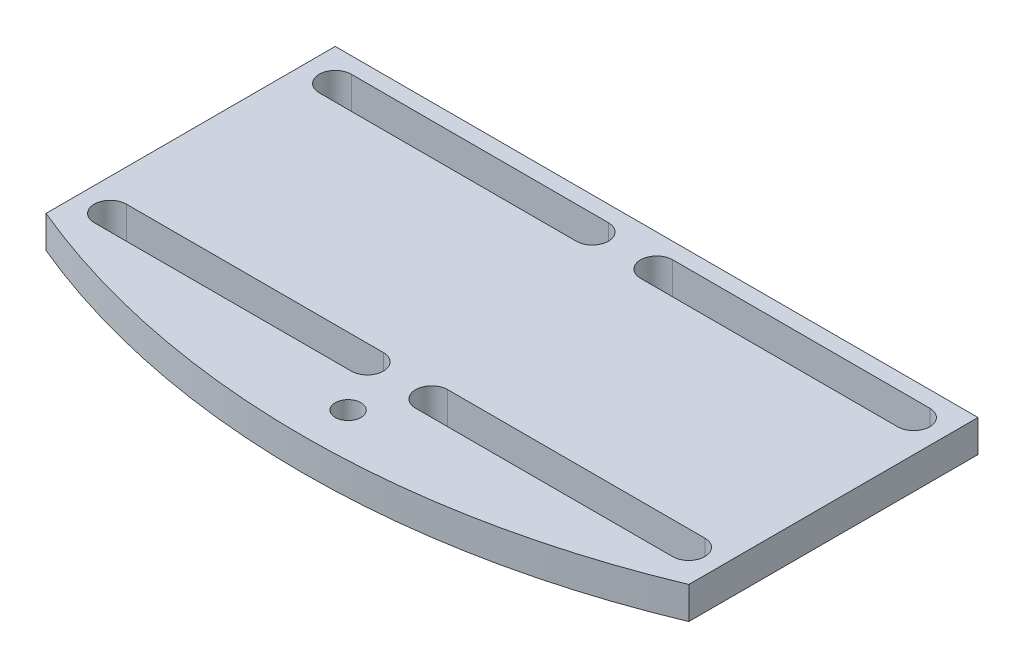
SolidWorks part; units mm, degrees
ref_plane "Front Plane" through (0, 0, 0) normal (0, 0, 1) x (1, 0, 0)
ref_plane "Top Plane" through (0, 0, 0) normal (0, 1, 0) x (1, 0, 0)
ref_plane "Right Plane" through (0, 0, 0) normal (1, 0, 0) x (0, 0, -1)
sketch "Sketch1" plane through (0, 0, 0) normal (0, 1, 0) x (1, 0, 0)
  line L2 (50, -40) -> (50, 5)
  line L3 (50, 5) -> (-50, 5)
  line L4 (-50, -40) -> (-50, 5)
  arc A0 (-50, -40) -> (50, -40) centre (0, 80) ccw
  point P0 (0, 5)
  point P6 (0, -50)
  dimension "D1" = 100
  dimension "D2" = 45
  dimension "D3" = 5
  dimension "D4" = 10
extrude "Boss-Extrude1" add sketch "Sketch1" along normal blind 5
sketch "Sketch2" plane through (0, 5, 0) normal (0, 1, 0) x (1, 0, 0)
  line L0 (0, 20) -> (0, -20) construction
  line L3 (-45, 0) -> (-5, 0) construction
  line L4 (-45, -35) -> (-5, -35) construction
  line L5 (-45, -32.5) -> (-5, -32.5)
  line L6 (-45, -37.5) -> (-5, -37.5)
  line L7 (-45, 2.5) -> (-5, 2.5)
  line L8 (-45, -2.5) -> (-5, -2.5)
  arc A8 (-45, -32.5) -> (-45, -37.5) centre (-45, -35) ccw
  arc A9 (-5, -37.5) -> (-5, -32.5) centre (-5, -35) ccw
  arc A10 (-45, 2.5) -> (-45, -2.5) centre (-45, 0) ccw
  arc A11 (-5, -2.5) -> (-5, 2.5) centre (-5, 0) ccw
  point P7 (-25, -35)
  point P11 (0, 0)
  point P15 (-25, 0)
  dimension "D4" = 40
  dimension "D2" = 2.5
  dimension "D5" = 45
  dimension "D7" = 35
extrude "Cut-Extrude1" cut sketch "Sketch2" against normal up to next
mirror "Mirror1" about plane through (0, 0, 0) normal (1, 0, 0) of "Cut-Extrude1"
sketch "Sketch3" plane through (0, 5, 0) normal (0, 1, 0) x (1, 0, 0)
  circle A0 centre (0, -43) radius 2
  dimension "D1" = 4
  dimension "D2" = 43
extrude "Cut-Extrude2" cut sketch "Sketch3" against normal up to next
